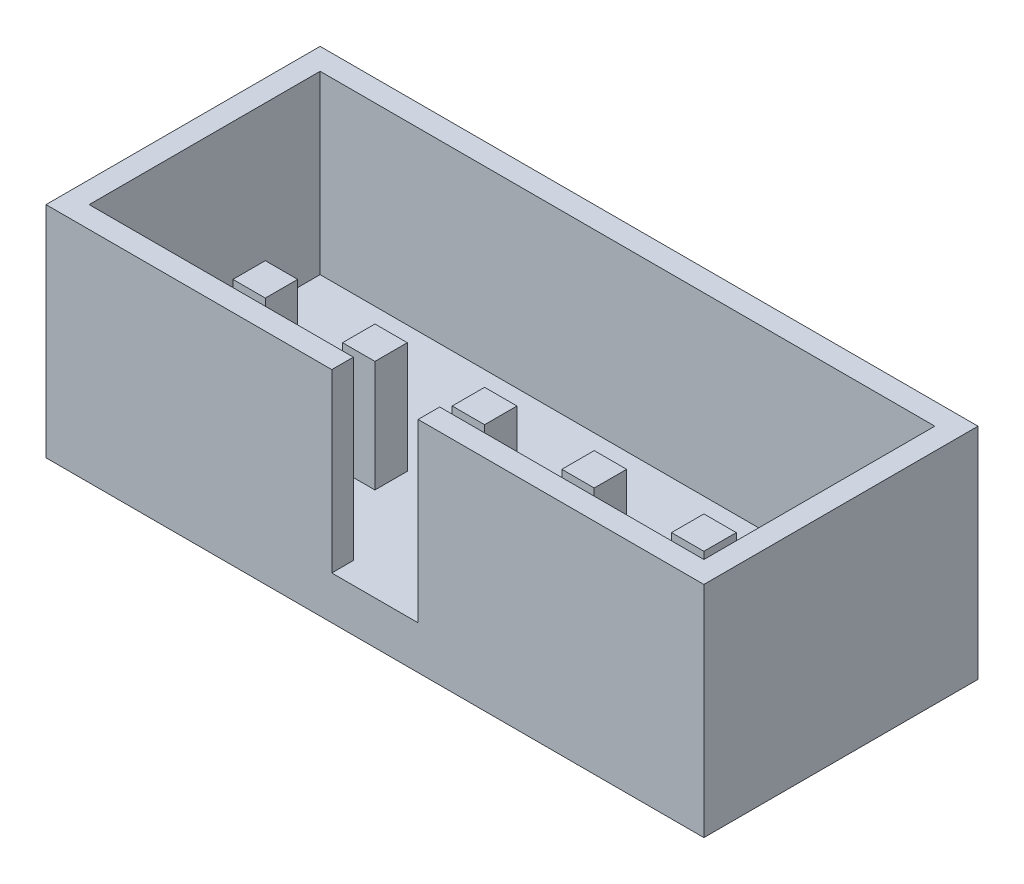
SolidWorks part; units mm, degrees
ref_plane "前视基准面" through (0, 0, 0) normal (0, 0, 1) x (1, 0, 0)
ref_plane "上视基准面" through (0, 0, 0) normal (0, 1, 0) x (1, 0, 0)
ref_plane "右视基准面" through (0, 0, 0) normal (1, 0, 0) x (0, 0, -1)
sketch "草图1" plane through (0, 0, 0) normal (0, 1, 0) x (1, 0, 0)
  line L0 (0, 7.1914) -> (0, -5.4429) construction
  line L1 (-7.62, 3.175) -> (7.62, 3.175)
  line L2 (-7.62, 3.175) -> (-7.62, -3.175)
  line L3 (-7.62, -3.175) -> (7.62, -3.175)
  line L4 (7.62, 3.175) -> (7.62, -3.175)
  line L5 (-10.6234, 0) -> (16.1963, 0) construction
  dimension "D1" = 15.24
  dimension "D2" = 6.35
extrude "拉伸1" add sketch "草图1" along normal blind 5.08
sketch "草图2" plane through (0, 5.08, 0) normal (0, 1, 0) x (-1, 0, 0)
  line L8 (7.12, -2.675) -> (7.12, 2.675)
  line L9 (7.12, 2.675) -> (-7.12, 2.675)
  line L10 (-7.12, 2.675) -> (-7.12, -2.675)
  line L11 (-7.12, -2.675) -> (7.12, -2.675)
  line L12 (7.12, -2.675) -> (7.12, 2.675)
  line L13 (7.12, 2.675) -> (-7.12, 2.675)
  line L14 (-7.12, 2.675) -> (-7.12, -2.675)
  line L15 (-7.12, -2.675) -> (7.12, -2.675)
  dimension "D1" = 0.5
extrude "切除-拉伸1" cut sketch "草图2" against normal offset from surface (4.08 mm away) 1 up to face at (0, 0, 0)
sketch "草图3" plane through (0, 0, 3.175) normal (0, 0, 1) x (1, 0, 0)
  line L0 (-7.62, 5.08) -> (7.62, 5.08) construction
  line L1 (-1, 5.08) -> (1, 5.08)
  line L2 (-1, 5.08) -> (-1, 1)
  line L3 (-1, 1) -> (1, 1)
  line L4 (1, 5.08) -> (1, 1)
  line L5 (7.12, 1) -> (-7.12, 1) construction
  line L6 (0, -1.5083) -> (0, 12.2426) construction
  dimension "D1" = 2
extrude "切除-拉伸2" cut sketch "草图3" against normal blind 1
sketch "草图4" plane through (0, 0, 0) normal (0, -1, 0) x (1, 0, 0)
  line L0 (7.6775, 0.635) -> (-8.5467, 0.635) construction
  line L1 (-7.62, 3.175) -> (7.62, 3.175) construction
  line L2 (0, -3.6953) -> (0, 4.0669) construction
  line L3 (-2.54, 2.1009) -> (-2.54, -0.7012) construction
  line L4 (-2.915, 1.01) -> (-2.165, 1.01)
  line L5 (-2.915, 1.01) -> (-2.915, 0.26)
  line L6 (-2.915, 0.26) -> (-2.165, 0.26)
  line L7 (-2.165, 1.01) -> (-2.165, 0.26)
  line L8 (-0.375, 1.01) -> (0.375, 1.01)
  line L9 (-0.375, 1.01) -> (-0.375, 0.26)
  line L10 (-0.375, 0.26) -> (0.375, 0.26)
  line L11 (0.375, 1.01) -> (0.375, 0.26)
  line L12 (2.165, 1.01) -> (2.915, 1.01)
  line L13 (2.165, 1.01) -> (2.165, 0.26)
  line L14 (2.165, 0.26) -> (2.915, 0.26)
  line L15 (2.915, 1.01) -> (2.915, 0.26)
  line L16 (-5.455, 1.01) -> (-4.705, 1.01)
  line L17 (-5.455, 1.01) -> (-5.455, 0.26)
  line L18 (-5.455, 0.26) -> (-4.705, 0.26)
  line L19 (-4.705, 1.01) -> (-4.705, 0.26)
  line L20 (4.705, 1.01) -> (5.455, 1.01)
  line L21 (4.705, 1.01) -> (4.705, 0.26)
  line L22 (4.705, 0.26) -> (5.455, 0.26)
  line L23 (5.455, 1.01) -> (5.455, 0.26)
  dimension "D1" = 2.54
  dimension "D2" = 0.75
  dimension "D3" = 0.75
  dimension "D4" = 2.54
  dimension "D5" = 4
extrude "拉伸2" add sketch "草图4" along normal blind 2 and the other way offset from surface (3.58 mm away) 1.5 other way up to face at (0, 5.08, 0.975)
